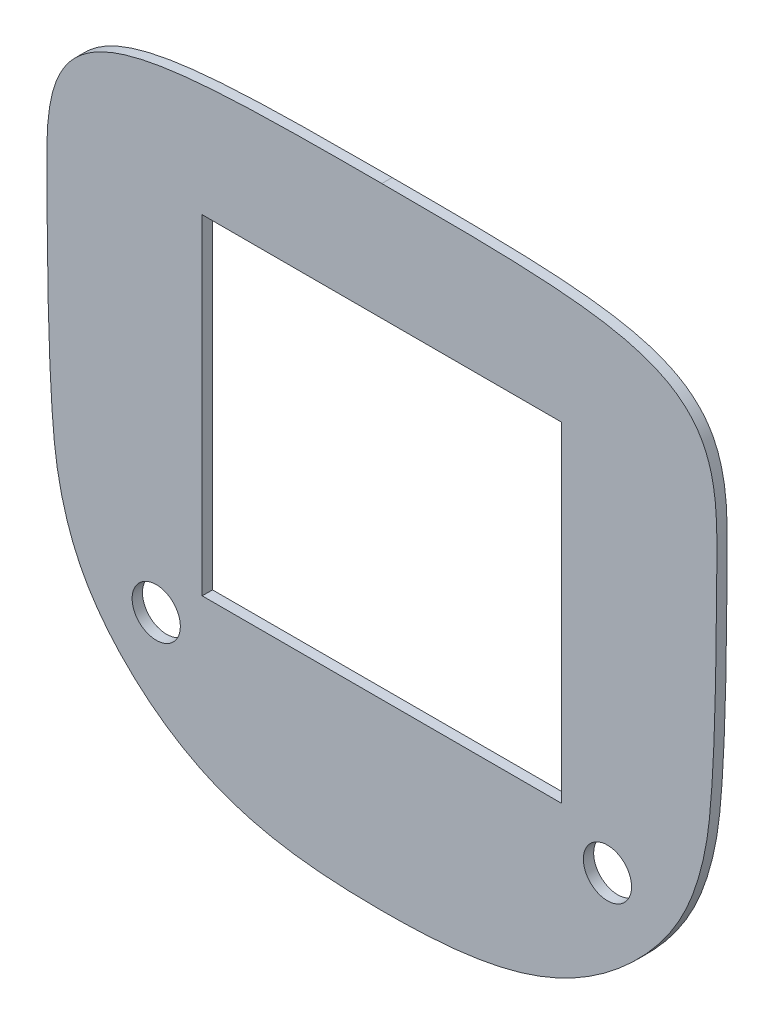
SolidWorks part; units mm, degrees
ref_plane "Front Plane" through (0, 0, 0) normal (0, 0, 1) x (1, 0, 0)
ref_plane "Top Plane" through (0, 0, 0) normal (0, 1, 0) x (1, 0, 0)
ref_plane "Right Plane" through (0, 0, 0) normal (1, 0, 0) x (0, 0, -1)
ref_plane "Plane1" through (0, 0, 100) normal (0, 0, -1) x (-1, 0, 0)
sketch "Sketch1" plane through (0, 0, 100) normal (0, 0, -1) x (-1, 0, 0)
  line L0 (0, 109.7056) -> (0, -73.1371) construction
  line L2 (-52.1541, 75.787) -> (52.1541, 75.787)
  line L3 (-52.1541, 75.787) -> (-52.1541, -20.0446)
  line L4 (-52.1541, -20.0446) -> (52.1541, -20.0446)
  line L5 (52.1541, 75.787) -> (52.1541, -20.0446)
  line L6 (-52.1541, 75.787) -> (52.1541, -20.0446) construction
  line L7 (-52.1541, -20.0446) -> (52.1541, 75.787) construction
  circle A0 centre (-65.5, -30.8878) radius 7
  circle A1 centre (65.5, -30.8878) radius 7
  spline S0 degree 3 poles (120.0442, -3042.1017) (366.3134, 126.0675) (163.9693, -79.8175) (-13.4407, -72.8192) (-16.7834, -72.6088) (-23.4392, -71.9641) (-26.7521, -71.5296) (-33.3376, -70.3562) (-36.61, -69.6165) (-40.6674, -68.4431) (-41.4772, -68.196) (-43.0934, -67.6755) (-43.9008, -67.4017) (-46.31, -66.5418) (-47.8892, -65.9204) (-52.5445, -63.9094) (-55.537, -62.3708) (-61.3063, -58.9085) (-64.0845, -56.9872) (-67.4275, -54.3545) (-68.0901, -53.8159) (-69.3935, -52.723) (-70.0355, -52.1678) (-71.9328, -50.4771) (-73.1598, -49.3164) (-76.728, -45.7341) (-78.9589, -43.2145) (-82.0396, -39.1995) (-83.0214, -37.8212) (-84.8841, -34.9749) (-85.7674, -33.501) (-88.2046, -29.0237) (-89.5634, -25.9428) (-91.2398, -21.1907) (-91.7446, -19.5872) (-92.6604, -16.3463) (-93.0697, -14.7082) (-93.7952, -11.3985) (-94.1118, -9.723) (-94.6517, -6.3658) (-94.8768, -4.683) (-95.2393, -1.3093) (-95.3906, 0.3804) (-95.6676, 3.7621) (-95.7898, 5.4545) (-96.0069, 8.8417) (-96.1016, 10.5367) (-96.2755, 13.928) (-96.3542, 15.6244) (-96.5678, 20.7138) (-96.6807, 24.1076) (-96.9534, 34.291) (-97.0459, 41.0827) (-97.1493, 51.27) (-97.1785, 54.6658) (-97.2277, 59.7595) (-97.2458, 61.4574) (-97.2868, 64.8533) (-97.3103, 66.5515) (-97.2904, 69.9429) (-97.2559, 71.6367) (-97.0958, 75.0177) (-96.9726, 76.705) (-96.5853, 80.0691) (-96.3204, 81.7458) (-95.8548, 83.8317) (-95.7548, 84.2484) (-95.5396, 85.0806) (-95.4241, 85.4969) (-95.0548, 86.7335) (-94.7779, 87.544) (-93.8439, 89.9287) (-93.0837, 91.4561) (-91.9173, 93.2675) (-91.6726, 93.6258) (-91.167, 94.3236) (-90.9058, 94.6639) (-90.0972, 95.6599) (-89.5251, 96.2905) (-88.3172, 97.4873) (-87.6813, 98.0535) (-86.6823, 98.8572) (-86.3418, 99.1176) (-85.6463, 99.6235) (-85.2903, 99.8697) (-83.4921, 101.0547) (-81.9897, 101.864) (-78.8918, 103.2801) (-77.2954, 103.8853) (-74.8499, 104.6822) (-74.0257, 104.9295) (-72.3778, 105.3877) (-71.5521, 105.5993) (-69.0705, 106.1898) (-67.4103, 106.5251) (-64.0815, 107.1133) (-62.4129, 107.3654) (-57.3979, 108.0286) (-54.0423, 108.3496) (-47.3172, 108.8523) (-43.9476, 109.0331) (-37.2, 109.3116) (-33.822, 109.4086) (-27.0609, 109.5527) (-23.6778, 109.5995) (253.3858, 112.2518) (527.5922, 23.6128) (784.5058, 2939.6821) knots -1.59089 -1.59089 -1.59089 -1.59089 0.03125 0.03125 0.0625 0.0625 0.09375 0.09375 0.125 0.125 0.132812 0.132812 0.140625 0.140625 0.15625 0.15625 0.1875 0.1875 0.21875 0.21875 0.226562 0.226562 0.234375 0.234375 0.25 0.25 0.28125 0.28125 0.296875 0.296875 0.3125 0.3125 0.34375 0.34375 0.359375 0.359375 0.375 0.375 0.390625 0.390625 0.40625 0.40625 0.421875 0.421875 0.4375 0.4375 0.453125 0.453125 0.46875 0.46875 0.5 0.5 0.5625 0.5625 0.59375 0.59375 0.609375 0.609375 0.625 0.625 0.640625 0.640625 0.65625 0.65625 0.671875 0.671875 0.675781 0.675781 0.679688 0.679688 0.6875 0.6875 0.703125 0.703125 0.707031 0.707031 0.710938 0.710938 0.71875 0.71875 0.726563 0.726563 0.730469 0.730469 0.734375 0.734375 0.75 0.75 0.765625 0.765625 0.773438 0.773438 0.78125 0.78125 0.796875 0.796875 0.8125 0.8125 0.84375 0.84375 0.875 0.875 0.90625 0.90625 0.9375 0.9375 3.466007 3.466007 3.466007 3.466007 only from (0, -73.1371) to (0, 109.7056)
  spline S1 degree 3 poles (0, -73.1371) (-3.3707, -73.1371) (-6.7344, -73.0838) (-13.4407, -72.8192) (-16.7834, -72.6088) (-23.4392, -71.9641) (-26.7521, -71.5296) (-33.3376, -70.3562) (-36.61, -69.6165) (-40.6674, -68.4431) (-41.4772, -68.196) (-43.0934, -67.6755) (-43.9008, -67.4017) (-46.31, -66.5418) (-47.8892, -65.9204) (-52.5445, -63.9094) (-55.537, -62.3708) (-61.3063, -58.9085) (-64.0845, -56.9872) (-67.4275, -54.3545) (-68.0901, -53.8159) (-69.3935, -52.723) (-70.0355, -52.1678) (-71.9328, -50.4771) (-73.1598, -49.3164) (-76.728, -45.7341) (-78.9589, -43.2145) (-82.0396, -39.1995) (-83.0214, -37.8212) (-84.8841, -34.9749) (-85.7674, -33.501) (-88.2046, -29.0237) (-89.5634, -25.9428) (-91.2398, -21.1907) (-91.7446, -19.5872) (-92.6604, -16.3463) (-93.0697, -14.7082) (-93.7952, -11.3985) (-94.1118, -9.723) (-94.6517, -6.3658) (-94.8768, -4.683) (-95.2393, -1.3093) (-95.3906, 0.3804) (-95.6676, 3.7621) (-95.7898, 5.4545) (-96.0069, 8.8417) (-96.1016, 10.5367) (-96.2755, 13.928) (-96.3542, 15.6244) (-96.5678, 20.7138) (-96.6807, 24.1076) (-96.9534, 34.291) (-97.0459, 41.0827) (-97.1493, 51.27) (-97.1785, 54.6658) (-97.2277, 59.7595) (-97.2458, 61.4574) (-97.2868, 64.8533) (-97.3103, 66.5515) (-97.2904, 69.9429) (-97.2559, 71.6367) (-97.0958, 75.0177) (-96.9726, 76.705) (-96.5853, 80.0691) (-96.3204, 81.7458) (-95.8548, 83.8317) (-95.7548, 84.2484) (-95.5396, 85.0806) (-95.4241, 85.4969) (-95.0548, 86.7335) (-94.7779, 87.544) (-93.8439, 89.9287) (-93.0837, 91.4561) (-91.9173, 93.2675) (-91.6726, 93.6258) (-91.167, 94.3236) (-90.9058, 94.6639) (-90.0972, 95.6599) (-89.5251, 96.2905) (-88.3172, 97.4873) (-87.6813, 98.0535) (-86.6823, 98.8572) (-86.3418, 99.1176) (-85.6463, 99.6235) (-85.2903, 99.8697) (-83.4921, 101.0547) (-81.9897, 101.864) (-78.8918, 103.2801) (-77.2954, 103.8853) (-74.8499, 104.6822) (-74.0257, 104.9295) (-72.3778, 105.3877) (-71.5521, 105.5993) (-69.0705, 106.1898) (-67.4103, 106.5251) (-64.0815, 107.1133) (-62.4129, 107.3654) (-57.3979, 108.0286) (-54.0423, 108.3496) (-47.3172, 108.8523) (-43.9476, 109.0331) (-37.2, 109.3116) (-33.822, 109.4086) (-27.0609, 109.5527) (-23.6778, 109.5995) (-13.5305, 109.6966) (-6.7653, 109.7056) (0, 109.7056) knots 0 0 0 0 0.03125 0.03125 0.0625 0.0625 0.09375 0.09375 0.125 0.125 0.132812 0.132812 0.140625 0.140625 0.15625 0.15625 0.1875 0.1875 0.21875 0.21875 0.226562 0.226562 0.234375 0.234375 0.25 0.25 0.28125 0.28125 0.296875 0.296875 0.3125 0.3125 0.34375 0.34375 0.359375 0.359375 0.375 0.375 0.390625 0.390625 0.40625 0.40625 0.421875 0.421875 0.4375 0.4375 0.453125 0.453125 0.46875 0.46875 0.5 0.5 0.5625 0.5625 0.59375 0.59375 0.609375 0.609375 0.625 0.625 0.640625 0.640625 0.65625 0.65625 0.671875 0.671875 0.675781 0.675781 0.679688 0.679688 0.6875 0.6875 0.703125 0.703125 0.707031 0.707031 0.710938 0.710938 0.71875 0.71875 0.726563 0.726563 0.730469 0.730469 0.734375 0.734375 0.75 0.75 0.765625 0.765625 0.773438 0.773438 0.78125 0.78125 0.796875 0.796875 0.8125 0.8125 0.84375 0.84375 0.875 0.875 0.90625 0.90625 0.9375 0.9375 1 1 1 1
  spline S2 degree 3 poles (0, -73.1371) (3.3707, -73.1371) (6.7344, -73.0838) (13.4407, -72.8192) (16.7834, -72.6088) (23.4392, -71.9641) (26.7521, -71.5296) (33.3376, -70.3562) (36.61, -69.6165) (40.6674, -68.4431) (41.4772, -68.196) (43.0934, -67.6755) (43.9008, -67.4017) (46.31, -66.5418) (47.8892, -65.9204) (52.5445, -63.9094) (55.537, -62.3708) (61.3063, -58.9085) (64.0845, -56.9872) (67.4275, -54.3545) (68.0901, -53.8159) (69.3935, -52.723) (70.0355, -52.1678) (71.9328, -50.4771) (73.1598, -49.3164) (76.728, -45.7341) (78.9589, -43.2145) (82.0396, -39.1995) (83.0214, -37.8212) (84.8841, -34.9749) (85.7674, -33.501) (88.2046, -29.0237) (89.5634, -25.9428) (91.2398, -21.1907) (91.7446, -19.5872) (92.6604, -16.3463) (93.0697, -14.7082) (93.7952, -11.3985) (94.1118, -9.723) (94.6517, -6.3658) (94.8768, -4.683) (95.2393, -1.3093) (95.3906, 0.3804) (95.6676, 3.7621) (95.7898, 5.4545) (96.0069, 8.8417) (96.1016, 10.5367) (96.2755, 13.928) (96.3542, 15.6244) (96.5678, 20.7138) (96.6807, 24.1076) (96.9534, 34.291) (97.0459, 41.0827) (97.1493, 51.27) (97.1785, 54.6658) (97.2277, 59.7595) (97.2458, 61.4574) (97.2868, 64.8533) (97.3103, 66.5515) (97.2904, 69.9429) (97.2559, 71.6367) (97.0958, 75.0177) (96.9726, 76.705) (96.5853, 80.0691) (96.3204, 81.7458) (95.8548, 83.8317) (95.7548, 84.2484) (95.5396, 85.0806) (95.4241, 85.4969) (95.0548, 86.7335) (94.7779, 87.544) (93.8439, 89.9287) (93.0837, 91.4561) (91.9173, 93.2675) (91.6726, 93.6258) (91.167, 94.3236) (90.9058, 94.6639) (90.0972, 95.6599) (89.5251, 96.2905) (88.3172, 97.4873) (87.6813, 98.0535) (86.6823, 98.8572) (86.3418, 99.1176) (85.6463, 99.6235) (85.2903, 99.8697) (83.4921, 101.0547) (81.9897, 101.864) (78.8918, 103.2801) (77.2954, 103.8853) (74.8499, 104.6822) (74.0257, 104.9295) (72.3778, 105.3877) (71.5521, 105.5993) (69.0705, 106.1898) (67.4103, 106.5251) (64.0815, 107.1133) (62.4129, 107.3654) (57.3979, 108.0286) (54.0423, 108.3496) (47.3172, 108.8523) (43.9476, 109.0331) (37.2, 109.3116) (33.822, 109.4086) (27.0609, 109.5527) (23.6778, 109.5995) (13.5305, 109.6966) (6.7653, 109.7056) (0, 109.7056) knots 0 0 0 0 0.03125 0.03125 0.0625 0.0625 0.09375 0.09375 0.125 0.125 0.132812 0.132812 0.140625 0.140625 0.15625 0.15625 0.1875 0.1875 0.21875 0.21875 0.226562 0.226562 0.234375 0.234375 0.25 0.25 0.28125 0.28125 0.296875 0.296875 0.3125 0.3125 0.34375 0.34375 0.359375 0.359375 0.375 0.375 0.390625 0.390625 0.40625 0.40625 0.421875 0.421875 0.4375 0.4375 0.453125 0.453125 0.46875 0.46875 0.5 0.5 0.5625 0.5625 0.59375 0.59375 0.609375 0.609375 0.625 0.625 0.640625 0.640625 0.65625 0.65625 0.671875 0.671875 0.675781 0.675781 0.679688 0.679688 0.6875 0.6875 0.703125 0.703125 0.707031 0.707031 0.710938 0.710938 0.71875 0.71875 0.726563 0.726563 0.730469 0.730469 0.734375 0.734375 0.75 0.75 0.765625 0.765625 0.773438 0.773438 0.78125 0.78125 0.796875 0.796875 0.8125 0.8125 0.84375 0.84375 0.875 0.875 0.90625 0.90625 0.9375 0.9375 1 1 1 1
  point P7 (0, 27.8712)
  dimension "D1" = 14
extrude "Boss-Extrude1" add sketch "Sketch1" along normal blind 3
